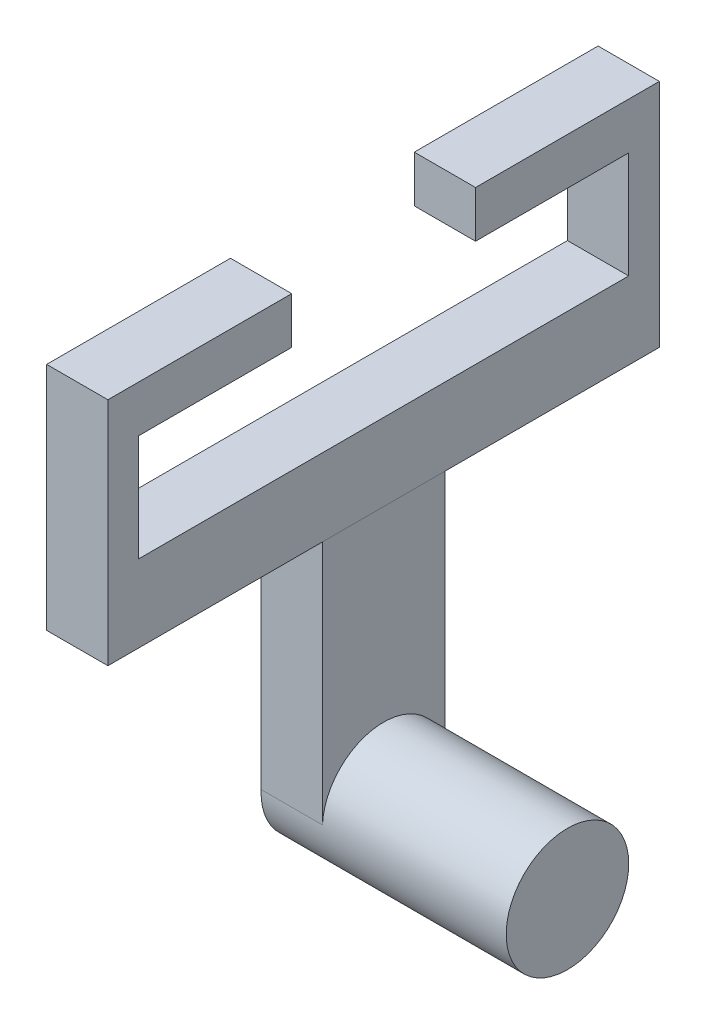
SolidWorks part; units mm, degrees
material "6061-T6 (SS)"
ref_plane "Front Plane" through (0, 0, 0) normal (0, 0, 1) x (1, 0, 0)
ref_plane "Top Plane" through (0, 0, 0) normal (0, 1, 0) x (1, 0, 0)
ref_plane "Right Plane" through (0, 0, 0) normal (1, 0, 0) x (0, 0, -1)
sketch "Sketch2" plane through (0, 0, 0) normal (1, 0, 0) x (0, 0, -1)
  circle A0 centre (0, 0) radius 12.7
  dimension "D1" = 25.4
extrude "Boss-Extrude1" add sketch "Sketch2" along normal blind 50.8 contours A0
sketch "Sketch3" plane through (0, 0, 0) normal (-1, 0, 0) x (0, 0, 1)
  line L1 (-12.6854, 0.6087) -> (12.7146, 0.6087)
  line L2 (-12.6854, 0.6087) -> (-12.6854, 51.4087)
  line L3 (-12.6854, 51.4087) -> (12.7146, 51.4087)
  line L4 (12.7146, 0.6087) -> (12.7146, 51.4087)
  circle A0 centre (0, 0) radius 12.7 construction
  point P6 (12.7575, 1.207)
  dimension "D1" = 25.4
  dimension "D2" = 50.8
extrude "Boss-Extrude2" add sketch "Sketch3" against normal blind 12.7
sketch "Sketch5" plane through (0, 0, 0) normal (1, 0, 0) x (0, 0, -1)
  line L1 (50.8, 67.3933) -> (-50.8, 67.3933)
  line L2 (50.8, 67.3933) -> (50.8, 51.3913)
  line L3 (50.8, 51.3913) -> (-50.8, 51.3913)
  line L4 (-50.8, 67.3933) -> (-50.8, 51.3913)
  line L5 (50.8, 67.3933) -> (-50.8, 51.3913) construction
  line L6 (50.8, 51.3913) -> (-50.8, 67.3933) construction
  point P0 (0, 59.3923)
  point P5 (0, 0)
  point P6 (0, 59.3923)
  point P8 (0, 59.3925)
  point P9 (0, 59.412)
  point P10 (0, 59.0414)
  point P11 (0, 59.0998)
  point P12 (0, 0)
  point P13 (0, 59.5429)
  point P15 (0, 59.8647)
  dimension "D1" = 101.6
  dimension "D2" = 16.002
extrude "Boss-Extrude3" add sketch "Sketch5" along normal blind 12.7 separate body
sketch "Sketch6" plane through (0, 0, 0) normal (1, 0, 0) x (0, 0, -1)
  line L1 (-50.8, 51.3913) -> (-57.15, 51.3913)
  line L2 (-50.8, 51.3913) -> (-50.8, 89.4913)
  line L3 (-50.8, 89.4913) -> (-57.15, 89.4913)
  line L4 (-57.15, 51.3913) -> (-57.15, 89.4913)
  line L5 (50.8, 51.3913) -> (57.15, 51.3913)
  line L6 (50.8, 51.3913) -> (50.8, 89.4913)
  line L7 (50.8, 89.4913) -> (57.15, 89.4913)
  line L8 (57.15, 51.3913) -> (57.15, 89.4913)
  dimension "D1" = 6.35
  dimension "D2" = 38.1
  dimension "D3" = 6.35
  dimension "D4" = 38.1
extrude "Boss-Extrude4" add sketch "Sketch6" along normal blind 12.7
sketch "Sketch7" plane through (0, 0, 0) normal (1, 0, 0) x (0, 0, -1)
  line L1 (-57.15, 89.4913) -> (-19.05, 89.4913)
  line L2 (-57.15, 89.4913) -> (-57.15, 99.1433)
  line L3 (-57.15, 99.1433) -> (-19.05, 99.1433)
  line L4 (-19.05, 89.4913) -> (-19.05, 99.1433)
  line L5 (57.15, 89.4913) -> (19.05, 89.4913)
  line L6 (57.15, 89.4913) -> (57.15, 99.1433)
  line L7 (57.15, 99.1433) -> (19.05, 99.1433)
  line L8 (19.05, 89.4913) -> (19.05, 99.1433)
  dimension "D1" = 38.1
  dimension "D2" = 38.1
  dimension "D3" = 9.652
  dimension "D4" = 9.652
extrude "Boss-Extrude5" add sketch "Sketch7" along normal blind 12.7
equation "\"d_A\"= 1.00in"
equation "\"t_B\"= 0.50in"
equation "\"h_B\"= 2.00in"
equation "\"h_C\" = 0.625in"
equation "\"L_C\"= 4.00in"
equation "\"L_D\" = 1.500in"
equation "\"h_E\"= 0.375in"
equation "\"L_E\"= 1.500in"
equation "\"W_B\"= \"d_A\""
equation "\"L_A\"= 2.00in"
equation "\"t_C\"= \"t_B\""
equation "\"t_D\"= \"t_B\""
equation "\"t_E\"= \"t_B\""
